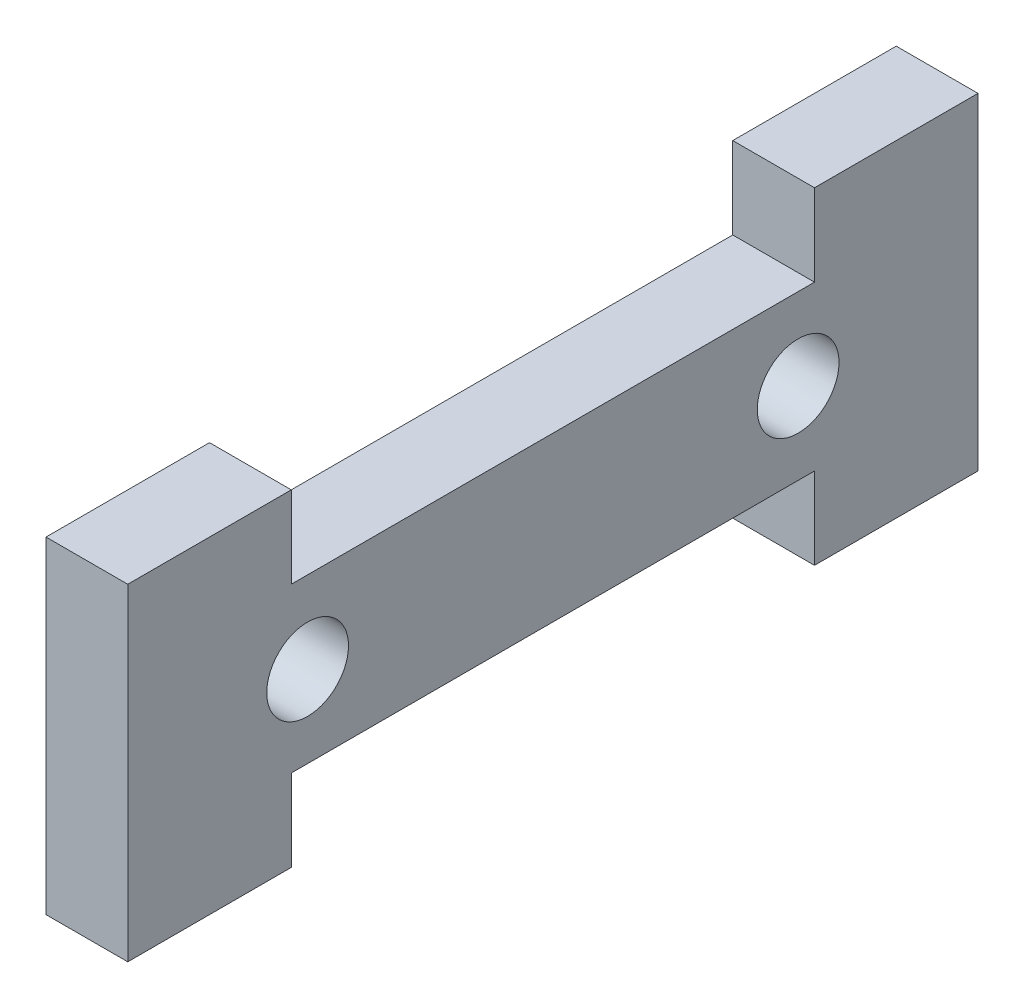
SolidWorks part; units mm, degrees
ref_plane "Front Plane" through (0, 0, 0) normal (0, 0, 1) x (1, 0, 0)
ref_plane "Top Plane" through (0, 0, 0) normal (0, 1, 0) x (1, 0, 0)
ref_plane "Right Plane" through (0, 0, 0) normal (1, 0, 0) x (0, 0, -1)
sketch "Sketch1" plane through (0, 0, 0) normal (1, 0, 0) x (0, 0, -1)
  line L0 (-20.32, 12.7) -> (-20.32, 6.35)
  line L5 (-33.02, 12.7) -> (-20.32, 12.7)
  line L6 (-33.02, 12.7) -> (-33.02, -12.7)
  line L7 (-33.02, -12.7) -> (-20.32, -12.7)
  line L8 (33.02, 12.7) -> (33.02, -12.7)
  line L9 (-20.32, 6.35) -> (20.32, 6.35)
  line L10 (20.32, 6.35) -> (20.32, 12.7)
  line L11 (-20.32, -12.7) -> (-20.32, -6.35)
  line L12 (-20.32, -6.35) -> (20.32, -6.35)
  line L13 (20.32, -6.35) -> (20.32, -12.7)
  line L14 (20.32, 12.7) -> (33.02, 12.7)
  line L15 (20.32, -12.7) -> (33.02, -12.7)
  circle A0 centre (0, 0) radius 36.322 construction
  circle A1 centre (-19.05, 0) radius 3.175
  circle A2 centre (19.05, 0) radius 3.175
  dimension "D1" = 72.644
  dimension "D8" = 6.35
  dimension "D9" = 6.35
  dimension "D2" = 25.4
  dimension "D3" = 12.7
  dimension "D4" = 33.02
  dimension "D5" = 33.02
  dimension "D6" = 19.05
  dimension "D7" = 19.05
  dimension "D10" = 6.35
  dimension "D11" = 6.35
  dimension "D12" = 12.7
  dimension "D13" = 12.7
  dimension "D14" = 12.7
  dimension "D15" = 12.7
extrude "Boss-Extrude1" add sketch "Sketch1" along normal blind 6.35
